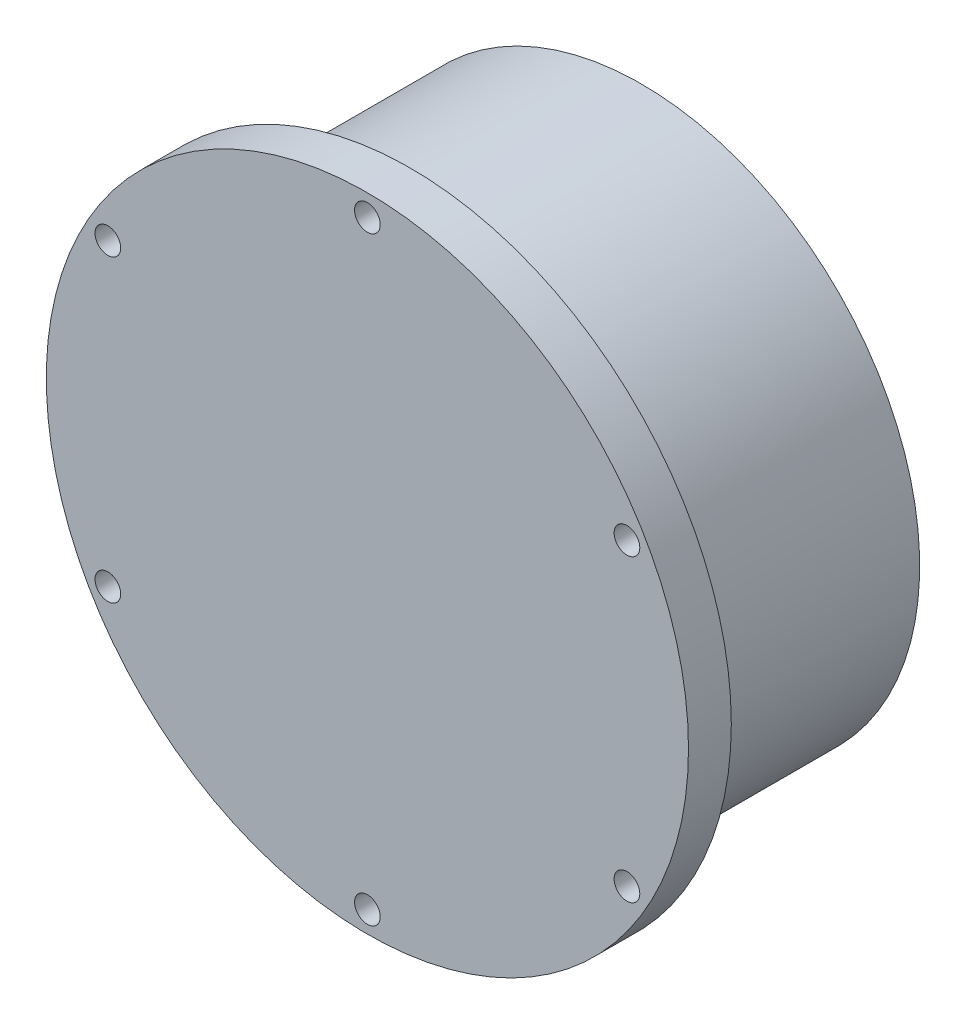
SolidWorks part; units mm, degrees
ref_plane "Front Plane" through (0, 0, 0) normal (0, 0, 1) x (1, 0, 0)
ref_plane "Top Plane" through (0, 0, 0) normal (0, 1, 0) x (1, 0, 0)
ref_plane "Right Plane" through (0, 0, 0) normal (1, 0, 0) x (0, 0, -1)
sketch "Sketch1" plane through (0, 0, 0) normal (0, 0, 1) x (1, 0, 0)
  circle A0 centre (0, 0) radius 37.5
  circle A1 centre (0, 35) radius 1.5
  circle A2 centre (30.3109, 17.5) radius 1.5
  circle A3 centre (30.3109, -17.5) radius 1.5
  circle A4 centre (0, -35) radius 1.5
  circle A5 centre (-30.3109, -17.5) radius 1.5
  circle A6 centre (-30.3109, 17.5) radius 1.5
  circle A7 centre (0, 0) radius 35 construction
  point P18 (0, 0)
  dimension "D1" = 75
  dimension "D2" = 3
  dimension "D3" = 70
  dimension "D4" = 6
extrude "Boss-Extrude1" add sketch "Sketch1" along normal blind 5
sketch "Sketch2" plane through (0, 0, 0) normal (0, 0, -1) x (-1, 0, 0)
  circle A0 centre (0, 0) radius 32.5
  dimension "D1" = 65
extrude "Boss-Extrude2" add sketch "Sketch2" along normal blind 27
sketch "Sketch3" plane through (0, 0, -27) normal (0, 0, -1) x (-1, 0, 0)
  circle A0 centre (0, 0) radius 12.5
  dimension "D1" = 25
extrude "Boss-Extrude3" add sketch "Sketch3" along normal blind 7.75
